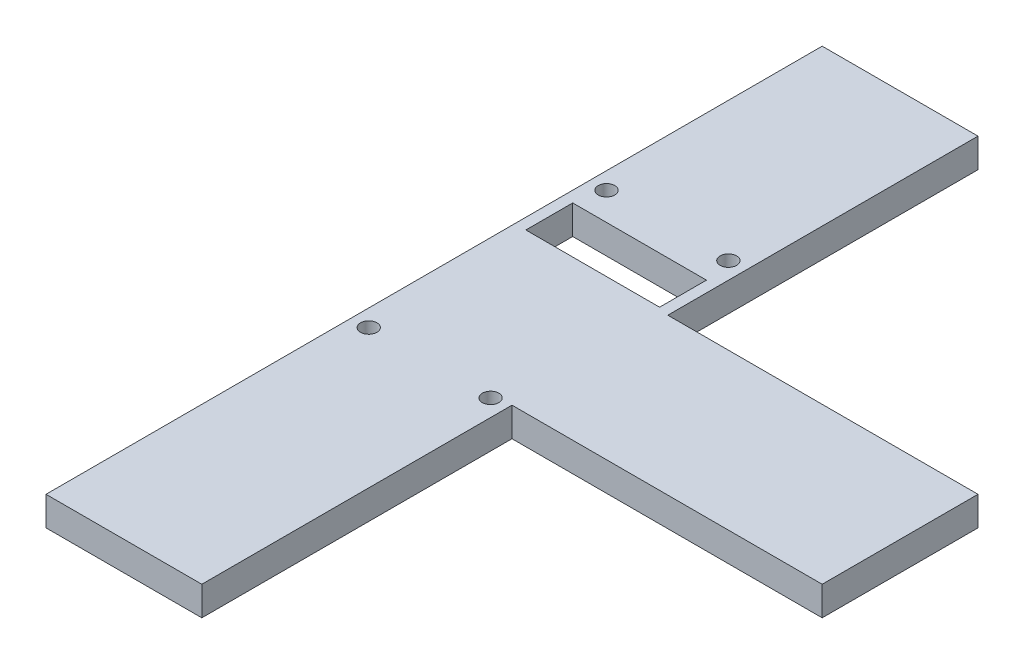
SolidWorks part; units mm, degrees
ref_plane "Front Plane" through (0, 0, 0) normal (0, 0, 1) x (1, 0, 0)
ref_plane "Top Plane" through (0, 0, 0) normal (0, 1, 0) x (1, 0, 0)
ref_plane "Right Plane" through (0, 0, 0) normal (1, 0, 0) x (0, 0, -1)
sketch "Sketch21" plane through (0, 0, 0) normal (0, 1, 0) x (1, 0, 0)
  line L21 (-16.06, -12.06) -> (-16.06, 20.06)
  line L22 (0, 84) -> (-16.06, 84)
  line L23 (-16.06, 84) -> (-16.06, 20.06)
  line L26 (-16.06, -12.06) -> (-16.06, -76)
  line L27 (-16.06, -76) -> (0, -76)
  line L28 (0, -76) -> (16.06, -76)
  line L29 (16.06, -76) -> (16.06, -12.06)
  line L30 (16.06, -12.06) -> (80, -12.06)
  line L31 (80, 20.06) -> (16.06, 20.06)
  line L32 (16.06, 20.06) -> (16.06, 84)
  line L33 (16.06, 84) -> (0, 84)
  line L36 (80, 4) -> (80, 20.06)
  line L37 (80, 4) -> (80, -12.06)
  line L38 (13.785, 20.64) -> (-13.785, 20.64)
  line L39 (13.785, 20.64) -> (13.785, 30.3)
  line L40 (13.785, 30.3) -> (-13.785, 30.3)
  line L41 (-13.785, 20.64) -> (-13.785, 30.3)
  circle A0 centre (-12.56, 36.04) radius 1.7
  circle A1 centre (12.56, 36.04) radius 1.7
  circle A2 centre (12.56, -12.97) radius 1.7
  circle A3 centre (-12.56, -12.97) radius 1.7
  dimension "D7" = 3.4
  dimension "D9" = 5.74
  dimension "D10" = 49.01
  dimension "D6" = 1.225
  dimension "D11" = 49.01
  dimension "D8" = 1.225
  dimension "D1" = 63.94
  dimension "D2" = 16.06
  dimension "D3" = 27.57
  dimension "D4" = 9.66
  dimension "D5" = 10.24
  dimension "D13" = 16.06
  dimension "D14" = 5.74
extrude "Boss-Extrude18" add sketch "Sketch21" along normal blind 6
